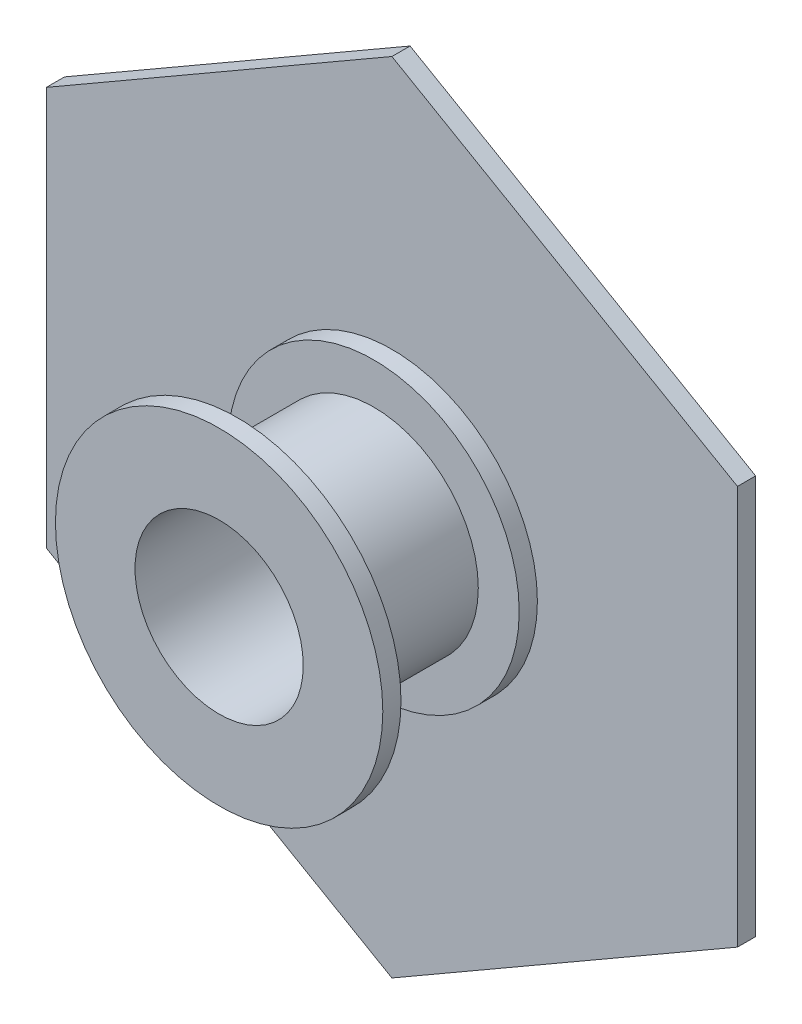
SolidWorks part; units mm, degrees
ref_plane "Front Plane" through (0, 0, 0) normal (0, 0, 1) x (1, 0, 0)
ref_plane "Top Plane" through (0, 0, 0) normal (0, 1, 0) x (1, 0, 0)
ref_plane "Right Plane" through (0, 0, 0) normal (1, 0, 0) x (0, 0, -1)
sketch "Sketch1" plane through (0, 0, 0) normal (0, 0, 1) x (1, 0, 0)
  line L1 (120.65, 69.6573) -> (0, 139.3146)
  line L2 (0, 139.3146) -> (-120.65, 69.6573)
  line L3 (-120.65, 69.6573) -> (-120.65, -69.6573)
  line L4 (-120.65, -69.6573) -> (0, -139.3146)
  line L5 (0, -139.3146) -> (120.65, -69.6573)
  line L6 (120.65, -69.6573) -> (120.65, 69.6573)
  circle A0 centre (0, 0) radius 120.65 construction
  dimension "D1" = 241.3
extrude "hex_base" add sketch "Sketch1" along normal blind 6.35
sketch "Sketch2" plane through (0, 0, 6.35) normal (0, 0, 1) x (1, 0, 0)
  circle A0 centre (0, 0) radius 29.3688
  dimension "D1" = 58.7375
extrude "ID" cut sketch "Sketch2" against normal through all
sketch "Sketch3" plane through (0, 0, 6.35) normal (0, 0, 1) x (1, 0, 0)
  circle A0 centre (0, 0) radius 36.5125
  circle A1 centre (0, 0) radius 29.3687 construction
  circle A2 centre (0, 0) radius 29.3688
  dimension "D1" = 73.025
extrude "pipe" add sketch "Sketch3" along normal blind 53.975
sketch "Sketch4" plane through (0, 0, 60.325) normal (0, 0, 1) x (1, 0, 0)
  circle A0 centre (0, 0) radius 57.15
  circle A1 centre (0, 0) radius 29.3687 construction
  circle A2 centre (0, 0) radius 29.3688
  dimension "D1" = 114.3
extrude "flange" add sketch "Sketch4" along normal blind 6.35
sketch "Sketch5" plane through (0, 0, 6.35) normal (0, 0, 1) x (1, 0, 0)
  circle A0 centre (0, 0) radius 36.5125 construction
  circle A1 centre (0, 0) radius 36.5125
  circle A2 centre (0, 0) radius 50.8
  dimension "D1" = 101.6
extrude "reinforcement" add sketch "Sketch5" along normal blind 6.35
